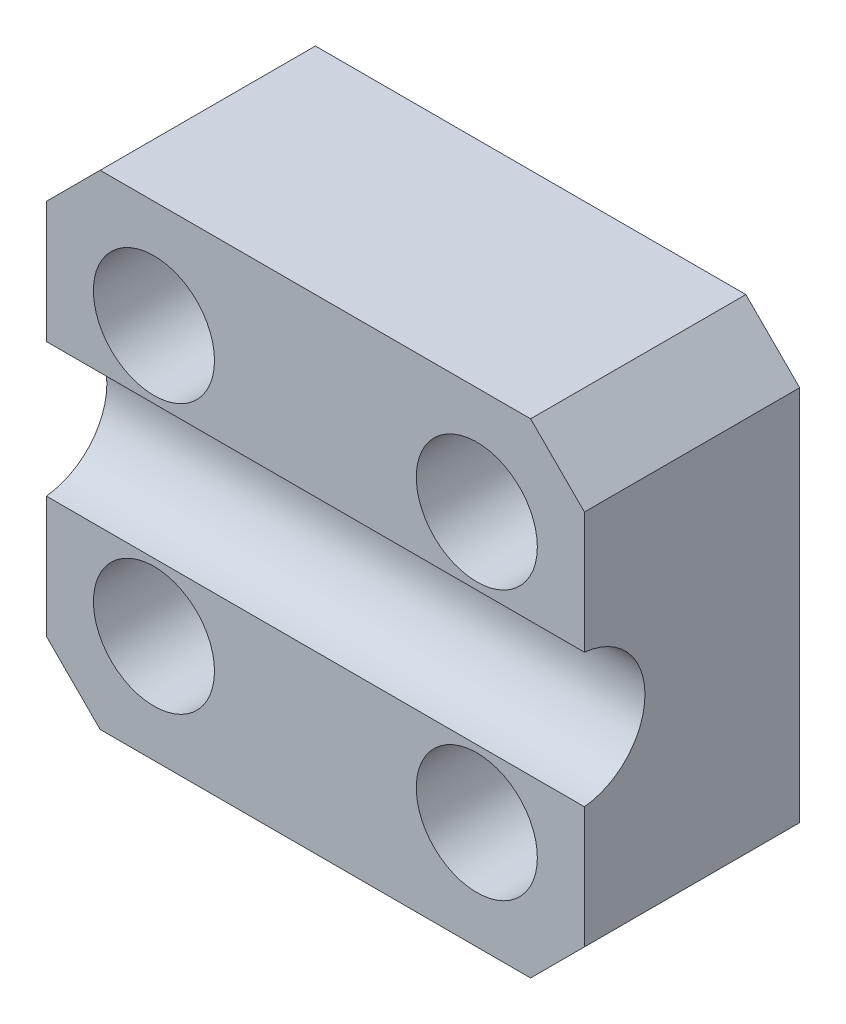
SolidWorks part; units mm, degrees
material "Printed PLA"
ref_plane "Front Plane" through (0, 0, 0) normal (0, 0, 1) x (1, 0, 0)
ref_plane "Top Plane" through (0, 0, 0) normal (0, 1, 0) x (1, 0, 0)
ref_plane "Right Plane" through (0, 0, 0) normal (1, 0, 0) x (0, 0, -1)
sketch "Sketch2" plane through (0, 0, 0) normal (0, 0, 1) x (1, 0, 0)
  line L0 (-10, 9) -> (10, -9) construction
  line L1 (-8, 9) -> (8, 9)
  line L2 (-10, 7) -> (-10, -7)
  line L3 (-8, -9) -> (8, -9)
  line L4 (10, 7) -> (10, -7)
  line L5 (6, -5) -> (-6, -5) construction
  line L6 (-6, -5) -> (-6, 5) construction
  line L7 (-6, 5) -> (6, 5) construction
  line L8 (6, 5) -> (6, -5) construction
  line L9 (6, -5) -> (-6, 5) construction
  line L10 (-10, 7) -> (-8, 9)
  line L11 (8, 9) -> (10, 7)
  line L12 (8, -9) -> (10, -7)
  line L13 (-10, -7) -> (-8, -9)
  circle A0 centre (-6, 5) radius 2.25
  circle A1 centre (-6, -5) radius 2.25
  circle A2 centre (6, 5) radius 2.25
  circle A3 centre (6, -5) radius 2.25
  point P2 (-10, -9)
  point P3 (10, 9)
  dimension "D5" = 4.5
  dimension "D1" = 20
  dimension "D2" = 18
  dimension "D3" = 12
  dimension "D4" = 10
extrude "Boss-Extrude1" add sketch "Sketch2" along normal blind 8
sketch "Sketch3" plane through (10, 0, 0) normal (1, 0, 0) x (0, 0, -1)
  line L0 (-8, -7) -> (-8, 7) construction
  line L1 (-8.25, 0) -> (0, 0) construction
  circle A0 centre (-8.25, 0) radius 2.5
  dimension "D1" = 5
  dimension "D2" = 0.25
extrude "Cut-Extrude1" cut sketch "Sketch3" against normal up to next
